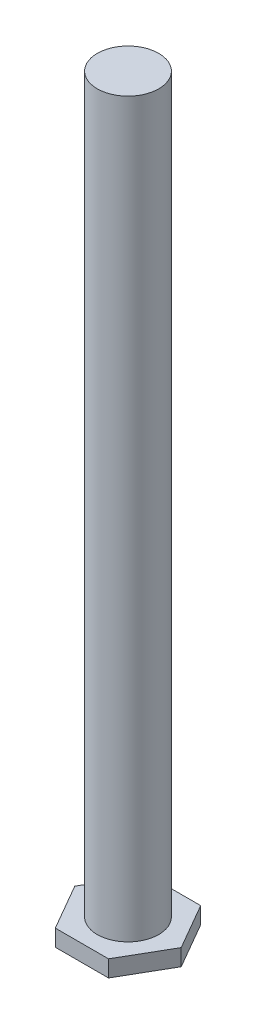
SolidWorks part; units mm, degrees
ref_plane "Front Plane" through (0, 0, 0) normal (0, 0, 1) x (1, 0, 0)
ref_plane "Top Plane" through (0, 0, 0) normal (0, 1, 0) x (1, 0, 0)
ref_plane "Right Plane" through (0, 0, 0) normal (1, 0, 0) x (0, 0, -1)
sketch "Sketch1" plane through (0, 0, 0) normal (0, 1, 0) x (1, 0, 0)
  line L1 (-10.4643, -1.2156) -> (-14.5338, 5.8329)
  line L2 (-14.5338, 5.8329) -> (-22.6727, 5.8329)
  line L3 (-22.6727, 5.8329) -> (-26.7421, -1.2156)
  line L4 (-26.7421, -1.2156) -> (-22.6727, -8.2641)
  line L5 (-22.6727, -8.2641) -> (-14.5338, -8.2641)
  line L6 (-14.5338, -8.2641) -> (-10.4643, -1.2156)
  circle A0 centre (-18.6032, -1.2156) radius 7.0485 construction
  dimension "D1" = 14.097
extrude "Boss-Extrude1" add sketch "Sketch1" along normal blind 2.54
sketch "Sketch2" plane through (0, 2.54, 0) normal (0, 1, 0) x (1, 0, 0)
  line L0 (-26.7421, -1.2156) -> (-10.4643, -1.2156) construction
  circle A0 centre (-18.6032, -1.2156) radius 4.699
  dimension "D1" = 9.398
extrude "Boss-Extrude2" add sketch "Sketch2" along normal blind 112.0394 separate body contours A0
